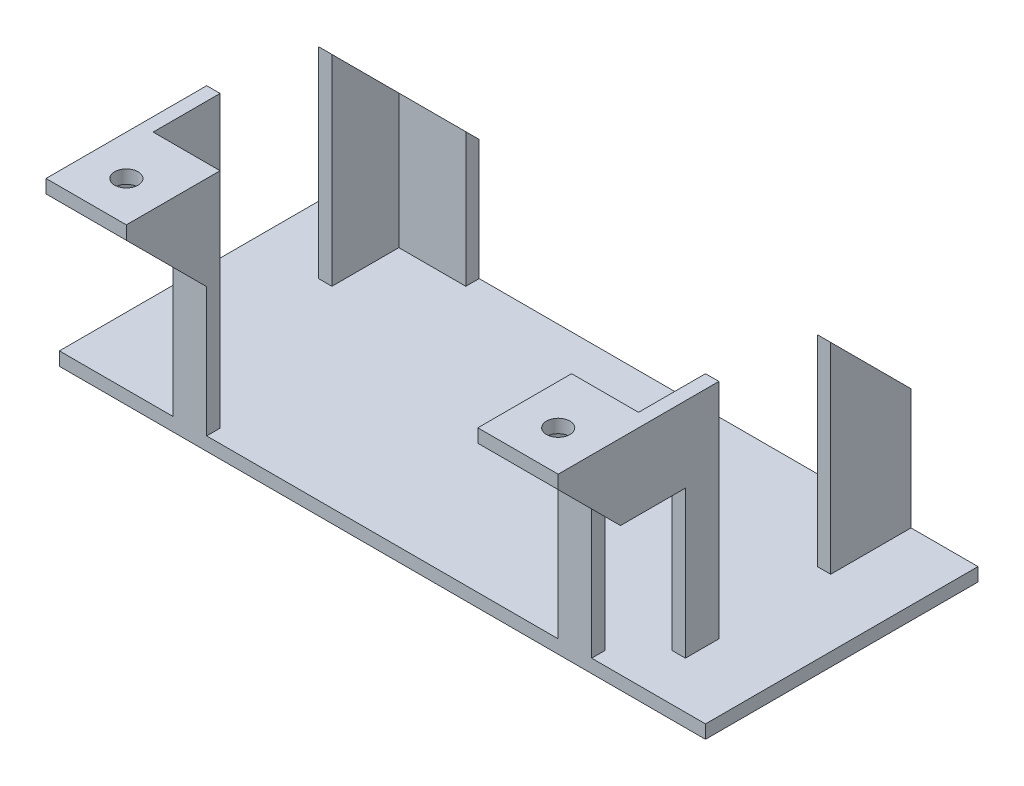
SolidWorks part; units mm, degrees
ref_plane "Alzado" through (0, 0, 0) normal (0, 0, 1) x (1, 0, 0)
ref_plane "Planta" through (0, 0, 0) normal (0, 1, 0) x (1, 0, 0)
ref_plane "Vista lateral" through (0, 0, 0) normal (1, 0, 0) x (0, 0, -1)
sketch "Croquis1" plane through (0, 0, 0) normal (0, 1, 0) x (1, 0, 0)
  line L6 (-38.25, 20.35) -> (38.25, 20.35)
  line L10 (-38.25, 20.35) -> (-38.25, -20.35)
  line L15 (-38.25, -20.35) -> (38.25, -20.35)
  line L16 (38.25, 20.35) -> (38.25, -20.35)
  line L17 (-38.25, 20.35) -> (38.25, -20.35) construction
  line L18 (-38.25, -20.35) -> (38.25, 20.35) construction
  point P0 (0, 0)
  dimension "D1" = 40.7
  dimension "D2" = 76.5
extrude "Saliente-Extruir1" add sketch "Croquis1" along normal blind 2
sketch "Croquis2" plane through (0, 2, 0) normal (0, 1, 0) x (1, 0, 0)
  line L0 (-26.25, 20.35) -> (-26.25, 18.35)
  line L1 (38.25, 20.35) -> (-38.25, 20.35) construction
  line L2 (-26.25, 18.35) -> (-36.25, 18.35)
  line L3 (-36.25, 18.35) -> (-36.25, 8.35)
  line L4 (-36.25, 8.35) -> (-38.25, 8.35)
  line L5 (-38.25, 20.35) -> (-38.25, -20.35) construction
  line L6 (-38.25, 8.35) -> (-38.25, 20.35)
  line L7 (-38.25, 20.35) -> (-26.25, 20.35)
  line L8 (-38.25, -8.35) -> (-38.25, -20.35)
  line L9 (-38.25, -20.35) -> (-26.25, -20.35)
  line L10 (-38.25, -20.35) -> (38.25, -20.35) construction
  line L11 (-26.25, -20.35) -> (-26.25, -18.35)
  line L12 (-26.25, -18.35) -> (-36.25, -18.35)
  line L13 (-36.25, -18.35) -> (-36.25, -8.35)
  line L14 (-36.25, -8.35) -> (-38.25, -8.35)
  line L15 (0, -27.7516) -> (0, 24.9459) construction
  line L16 (-31.25, 18.35) -> (-31.25, 20.35)
  line L17 (-36.25, 13.35) -> (-38.25, 13.35)
  line L18 (36.25, -8.35) -> (38.25, -8.35)
  line L19 (36.25, -18.35) -> (36.25, -8.35)
  line L20 (26.25, -18.35) -> (36.25, -18.35)
  line L21 (26.25, -20.35) -> (26.25, -18.35)
  line L22 (38.25, -20.35) -> (26.25, -20.35)
  line L23 (38.25, -8.35) -> (38.25, -20.35)
  line L24 (36.25, 13.35) -> (38.25, 13.35)
  line L25 (38.25, 8.35) -> (38.25, 20.35)
  line L26 (36.25, 8.35) -> (38.25, 8.35)
  line L27 (36.25, 18.35) -> (36.25, 8.35)
  line L28 (38.25, 20.35) -> (26.25, 20.35)
  line L29 (26.25, 18.35) -> (36.25, 18.35)
  line L30 (26.25, 20.35) -> (26.25, 18.35)
  line L31 (31.25, 18.35) -> (31.25, 20.35)
  line M12 (38.25, -20.35) -> (38.25, 20.35)
  line M13 (38.25, 20.35) -> (-38.25, 20.35)
  line M14 (-38.25, 20.35) -> (-38.25, -20.35)
  line M15 (-38.25, -20.35) -> (38.25, -20.35)
  dimension "D1" = 12
  dimension "D2" = 12
  dimension "D3" = 12
  dimension "D4" = 12
  dimension "D5" = 2
  dimension "D6" = 2
  dimension "D7" = 2
  dimension "D8" = 2
extrude "Saliente-Extruir2" add sketch "Croquis2" along normal blind 33.3 contours L13 L14 L11 L12 M14 M15 | L3 L17 L6 L4 | L16 L2 L0 M13 | L29 L31 L28 L30 | L24 L27 L26 M12 | L21 L18 L19 L20 M15 M12
sketch "Croquis3" plane through (0, 0, 20.35) normal (0, 0, 1) x (1, 0, 0)
  line L0 (-26.25, 35.3) -> (-26.25, 2) construction
  line L1 (-38.25, 35.3) -> (-26.25, 35.3)
  line L2 (-38.25, 35.3) -> (-38.25, 33.3)
  line L3 (-38.25, 33.3) -> (-26.25, 33.3)
  line L4 (-26.25, 35.3) -> (-26.25, 33.3)
  line L5 (38.25, 35.3) -> (38.25, 0) construction
  line L6 (26.25, 35.3) -> (38.25, 35.3)
  line L7 (26.25, 35.3) -> (26.25, 33.3)
  line L8 (26.25, 33.3) -> (38.25, 33.3)
  line L9 (38.25, 35.3) -> (38.25, 33.3)
  dimension "D1" = 2
  dimension "D2" = 2
extrude "Saliente-Extruir3" add sketch "Croquis3" along normal blind 12
sketch "Croquis4" plane through (-38.25, 0, 0) normal (-1, 0, 0) x (0, 0, 1)
  line L0 (32.35, 33.3) -> (20.35, 21.3)
  line L1 (20.35, 33.3) -> (20.35, 0) construction
  dimension "D1" = 16.9706
rib "Nervio2" sketch "Croquis4" sketch "Croquis4" thickness 2 extrusion direction parallel to sketch draft on no parameters "D1"=2
sketch "Croquis5" plane through (-26.25, 0, 0) normal (1, 0, 0) x (0, 0, -1)
  line L0 (-32.35, 33.3) -> (-20.35, 21.3)
rib "Nervio7" sketch "Croquis5" sketch "Croquis5" thickness 2 extrusion direction parallel to sketch draft on no parameters "D1"=2
sketch "Croquis6" plane through (26.25, 0, 0) normal (-1, 0, 0) x (0, 0, 1)
  line L0 (32.35, 33.3) -> (20.35, 21.3)
rib "Nervio8" sketch "Croquis6" sketch "Croquis6" thickness 2 extrusion direction parallel to sketch draft on no parameters "D1"=2
sketch "Croquis7" plane through (38.25, 0, 0) normal (1, 0, 0) x (0, 0, -1)
  line L0 (-32.35, 33.3) -> (-20.35, 21.3)
rib "Nervio9" sketch "Croquis7" sketch "Croquis7" thickness 2 extrusion direction parallel to sketch draft on no parameters "D1"=2
sketch "Croquis8" plane through (0, 35.3, 0) normal (0, 1, 0) x (1, 0, 0)
  line L0 (-32.25, -32.35) -> (-32.25, -26.35) construction
  line L1 (-26.25, -32.35) -> (-38.25, -32.35) construction
  line L2 (32.25, -32.35) -> (32.25, -26.35) construction
  line L3 (38.25, -32.35) -> (26.25, -32.35) construction
  circle A0 centre (-32.25, -26.35) radius 1.75
  circle A1 centre (32.25, -26.35) radius 1.75
  dimension "D2" = 3.5
  dimension "D1" = 6
extrude "Cortar-Extruir2" cut sketch "Croquis8" against normal blind 12
sketch "Croquis9" plane through (38.25, 0, 0) normal (1, 0, 0) x (0, 0, -1)
  line L0 (13.35, 35.3) -> (13.35, 2) construction
  line L1 (8.35, 35.3) -> (13.35, 35.3)
  line L2 (8.35, 35.3) -> (8.35, 33.3)
  line L3 (8.35, 33.3) -> (13.35, 33.3)
  line L4 (13.35, 35.3) -> (13.35, 33.3)
  dimension "D1" = 2
extrude "Saliente-Extruir4" add sketch "Croquis9" along normal blind 8
sketch "Croquis10" plane through (-38.25, 0, 0) normal (-1, 0, 0) x (0, 0, 1)
  line L0 (-8.35, 35.3) -> (-8.35, 2) construction
  line L1 (-13.35, 35.3) -> (-8.35, 35.3)
  line L2 (-13.35, 35.3) -> (-13.35, 33.3)
  line L3 (-13.35, 33.3) -> (-8.35, 33.3)
  line L4 (-8.35, 35.3) -> (-8.35, 33.3)
  dimension "D1" = 2
extrude "Saliente-Extruir5" add sketch "Croquis10" along normal blind 8
sketch "Croquis11" plane through (0, 0, -20.35) normal (0, 0, -1) x (-1, 0, 0)
  line L0 (31.25, 35.3) -> (31.25, 2) construction
  line L1 (-31.25, 35.3) -> (-26.25, 35.3)
  line L2 (-31.25, 35.3) -> (-31.25, 33.3)
  line L3 (-31.25, 33.3) -> (-26.25, 33.3)
  line L4 (-26.25, 35.3) -> (-26.25, 33.3)
  line L5 (26.25, 35.3) -> (31.25, 35.3)
  line L6 (26.25, 35.3) -> (26.25, 33.3)
  line L7 (26.25, 33.3) -> (31.25, 33.3)
  line L8 (31.25, 35.3) -> (31.25, 33.3)
  dimension "D1" = 2
extrude "Saliente-Extruir7" add sketch "Croquis11" along normal blind 8
sketch "Croquis12" plane through (-38.25, 0, 0) normal (-1, 0, 0) x (0, 0, 1)
  line L0 (-8.35, 35.3) -> (-8.35, 32) construction
  line L1 (-8.35, 33.3) -> (-8.35, 2) construction
  line L2 (-8.35, 32) -> (-8.35, 35.3)
  line L3 (-8.35, 35.3) -> (-28.35, 35.3)
  line L4 (-28.35, 35.3) -> (-28.35, 12)
  line L5 (-28.35, 12) -> (-8.35, 32)
  dimension "D1" = 3.3
  dimension "D2" = 45
sketch "Croquis13" plane through (0, 2, 0) normal (0, 1, 0) x (1, 0, 0)
  line L0 (-38.25, 13.35) -> (-38.25, 20.35)
  line L1 (-38.25, 20.35) -> (-31.25, 20.35)
  line L2 (-31.25, 20.35) -> (-31.25, 18.35)
  line L3 (-31.25, 18.35) -> (-36.25, 18.35)
  line L5 (-36.25, 13.35) -> (-38.25, 13.35)
  line L6 (-36.25, 13.35) -> (-36.25, 18.35)
  line L7 (0, 0) -> (0, 29.2686) construction
  line L8 (31.25, 20.35) -> (31.25, 18.35)
  line L9 (31.25, 18.35) -> (36.25, 18.35)
  line L10 (36.25, 13.35) -> (38.25, 13.35)
  line L11 (36.25, 13.35) -> (36.25, 18.35)
  line L12 (38.25, 13.35) -> (38.25, 20.35)
  line L13 (38.25, 20.35) -> (31.25, 20.35)
extrude "Saliente-Extruir8" add sketch "Croquis13" along normal up to surface (33.3 mm away) up to face at (-28.75, 35.3, -23.35)
extrude "Cortar-Extruir5" cut sketch "Croquis12" against normal through all from surface at 8 starting at face at (-46.25, 34.3, -10.85)
sketch "Croquis14" plane through (0, 2, 0) normal (0, 1, 0) x (1, 0, 0)
  line L0 (-36.25, -13.35) -> (-38.25, -13.35)
  line L1 (-36.25, -18.35) -> (-36.25, -8.35) construction
  line L2 (-38.25, -8.35) -> (-38.25, -32.35) construction
  line L3 (-38.25, -13.35) -> (-38.25, -20.35)
  line L4 (-36.25, -13.35) -> (-36.25, -18.35)
  line L5 (-36.25, -18.35) -> (-31.25, -18.35)
  line L6 (-26.25, -18.35) -> (-36.25, -18.35) construction
  line L7 (-31.25, -18.35) -> (-31.25, -20.35)
  line L8 (-31.25, -20.35) -> (-38.25, -20.35)
  line L9 (0, -20.35) -> (0, -6.0531) construction
  line L10 (-26.25, -20.35) -> (26.25, -20.35) construction
  line L11 (31.25, -18.35) -> (31.25, -20.35)
  line L12 (36.25, -18.35) -> (31.25, -18.35)
  line L13 (31.25, -20.35) -> (38.25, -20.35)
  line L14 (38.25, -13.35) -> (38.25, -20.35)
  line L15 (36.25, -13.35) -> (38.25, -13.35)
  line L16 (36.25, -13.35) -> (36.25, -18.35)
extrude "Cortar-Extruir6" cut sketch "Croquis14" along normal blind 22
sketch "Croquis15" plane through (0, 0, 20.35) normal (0, 0, 1) x (1, 0, 0)
  line L1 (-38.25, 21.3) -> (-36.25, 21.3)
  line L2 (-38.25, 21.3) -> (-38.25, 24)
  line L3 (-38.25, 24) -> (-36.25, 24)
  line L4 (-36.25, 21.3) -> (-36.25, 24)
  line L5 (38.25, 21.3) -> (36.25, 21.3)
  line L6 (38.25, 21.3) -> (38.25, 24)
  line L7 (38.25, 24) -> (36.25, 24)
  line L8 (36.25, 21.3) -> (36.25, 24)
extrude "Cortar-Extruir7" cut sketch "Croquis15" along normal blind 15
sketch "Croquis16" plane through (-38.25, 0, 0) normal (-1, 0, 0) x (0, 0, 1)
  line L1 (-20.35, 0) -> (20.35, 0)
  line L2 (-20.35, 0) -> (-20.35, 2)
  line L3 (-20.35, 2) -> (20.35, 2)
  line L4 (20.35, 0) -> (20.35, 2)
extrude "Saliente-Extruir9" add sketch "Croquis16" along normal blind 10
sketch "Croquis17" plane through (38.25, 0, 0) normal (1, 0, 0) x (0, 0, -1)
  line L1 (20.35, 0) -> (-20.35, 0)
  line L2 (20.35, 0) -> (20.35, 2)
  line L3 (20.35, 2) -> (-20.35, 2)
  line L4 (-20.35, 0) -> (-20.35, 2)
extrude "Saliente-Extruir10" add sketch "Croquis17" along normal blind 10
